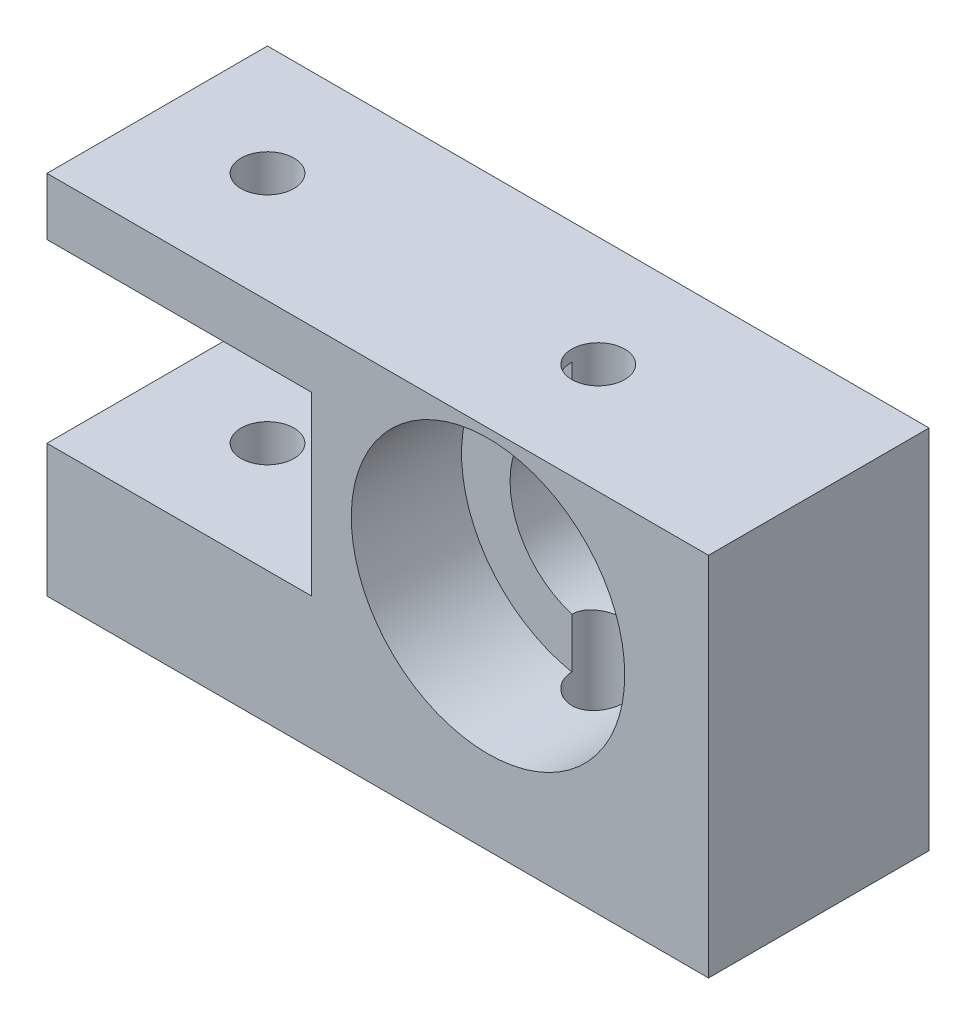
SolidWorks part; units mm, degrees
ref_plane "前视基准面" through (0, 0, 0) normal (0, 0, 1) x (1, 0, 0)
ref_plane "上视基准面" through (0, 0, 0) normal (0, 1, 0) x (1, 0, 0)
ref_plane "右视基准面" through (0, 0, 0) normal (1, 0, 0) x (0, 0, -1)
other "Configuration Table"
sketch "草图1" plane through (0, 0, 0) normal (0, 0, 1) x (1, 0, 0)
  line L1 (-10, -5) -> (10, -5)
  line L2 (-10, -5) -> (-10, 5)
  line L3 (-10, 5) -> (10, 5)
  line L4 (10, -5) -> (10, 5)
  line L5 (-10, -5) -> (10, 5) construction
  line L6 (-10, 5) -> (10, -5) construction
  circle A1 centre (0, 0) radius 3.1
  point P0 (0, 0)
  dimension "D1" = 10
  dimension "D3" = 6.2
  dimension "D2" = 20
extrude "凸台-拉伸1" add sketch "草图1" along normal blind 2.5 contours L1 L4 L3 L2 A1
sketch "草图2" plane through (0, 0, 0) normal (0, 0, -1) x (-1, 0, 0)
  line L0 (10, -5) -> (10, 5) construction
  line L1 (10, -5) -> (-10, -5)
  line L2 (10, -5) -> (10, 5)
  line L3 (10, 5) -> (-10, 5)
  line L4 (-10, -5) -> (-10, 5)
  line L5 (10, -5) -> (-10, -5) construction
  line L6 (10, 5) -> (-10, 5) construction
  line L12 (-10, -5) -> (-10, 5) construction
extrude "凸台-拉伸2" add sketch "草图2" along normal blind 2.5
sketch "草图3" plane through (0, -5, 0) normal (0, -1, 0) x (1, 0, 0)
  line L0 (0, -2.5) -> (0, 2.5) construction
  line L1 (10, -2.5) -> (-10, -2.5) construction
  line L2 (-10, 2.5) -> (10, 2.5) construction
  line L3 (10, 0) -> (-10, 0) construction
  line L4 (10, 2.5) -> (10, -2.5) construction
  line L5 (-10, 2.5) -> (-10, -2.5) construction
  circle A0 centre (-7.5, 0) radius 0.6
  circle A1 centre (0, 0) radius 0.6
  dimension "D1" = 1.2
  dimension "D2" = 2.5
extrude "切除-拉伸1" cut sketch "草图3" against normal through all contours A0 | A1
sketch "草图4" plane through (0, 0, -2.5) normal (0, 0, -1) x (-1, 0, 0)
  line L1 (10, -2) -> (4, -2)
  line L2 (10, -2) -> (10, 2)
  line L3 (10, 2) -> (4, 2)
  line L4 (4, -2) -> (4, 2)
  line L6 (10, 0) -> (4, 0) construction
  line L7 (10, -5) -> (10, 5) construction
  dimension "D1" = 4
  dimension "D2" = 6
extrude "切除-拉伸2" cut sketch "草图4" against normal through all
sketch "草图5" plane through (0, 0, 2.5) normal (0, 0, 1) x (1, 0, 0)
  circle A0 centre (0, 0) radius 2
  dimension "D1" = 4
extrude "切除-拉伸3" cut sketch "草图5" against normal through all
sketch "草图6" plane through (0, 0, 2.5) normal (0, 0, 1) x (1, 0, 0)
  line L0 (-10, 5) -> (10, 5) construction
  line L1 (10, 5) -> (-10, 5)
  line L2 (10, 5) -> (10, 3.3)
  line L3 (10, 3.3) -> (-10, 3.3)
  line L4 (-10, 5) -> (-10, 3.3)
  line L5 (-10, 2) -> (-10, 5) construction
  line L6 (10, -5) -> (10, 5) construction
  dimension "D1" = 1.7
extrude "切除-拉伸4" cut sketch "草图6" against normal through all
sketch "草图7" plane through (0, 0, 2.5) normal (0, 0, 1) x (1, 0, 0)
  line L0 (-10, 3.3) -> (10, 3.3) construction
  line L1 (10, 3.3) -> (5, 3.3)
  line L2 (10, 3.3) -> (10, -5)
  line L3 (10, -5) -> (5, -5)
  line L4 (5, 3.3) -> (5, -5)
  line L5 (-10, -5) -> (10, -5) construction
  line L6 (10, -5) -> (10, 3.3) construction
  point P8 (9.1654, 3.3)
  dimension "D1" = 5
extrude "切除-拉伸5" cut sketch "草图7" against normal through all
